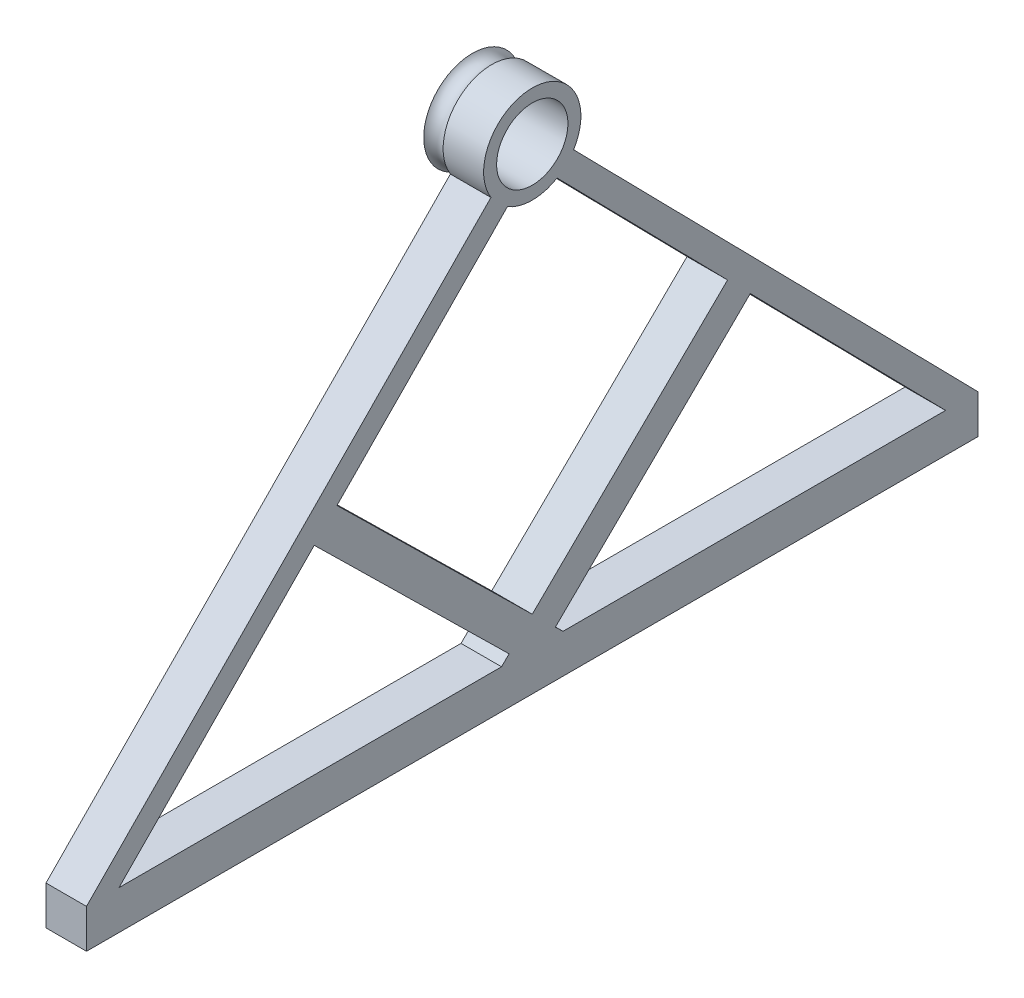
SolidWorks part; units mm, degrees
ref_plane "Front Plane" through (0, 0, 0) normal (0, 0, 1) x (1, 0, 0)
ref_plane "Top Plane" through (0, 0, 0) normal (0, 1, 0) x (1, 0, 0)
ref_plane "Right Plane" through (0, 0, 0) normal (1, 0, 0) x (0, 0, -1)
sketch "Sketch1" plane through (0, 0, 0) normal (0, 1, 0) x (1, 0, 0)
  line L1 (-152.5, -125) -> (152.5, -125)
  line L2 (-152.5, -125) -> (-152.5, 125)
  line L3 (-152.5, 125) -> (152.5, 125)
  line L4 (152.5, -125) -> (152.5, 125)
  line L5 (-152.5, -125) -> (152.5, 125) construction
  line L6 (-152.5, 125) -> (152.5, -125) construction
  line L7 (-165, -137.5) -> (165, -137.5)
  line L8 (-165, -137.5) -> (-165, 137.5)
  line L9 (-165, 137.5) -> (165, 137.5)
  line L10 (165, -137.5) -> (165, 137.5)
  line L11 (-165, -137.5) -> (165, 137.5) construction
  line L12 (-165, 137.5) -> (165, -137.5) construction
  point P0 (0, 0)
  point P5 (0, 0)
extrude "Boss-Extrude4" add sketch "Sketch1" along normal blind 12
sketch "Sketch2" plane through (165, 0, 0) normal (1, 0, 0) x (0, 0, -1)
  line L0 (0, 12) -> (0, 152) construction
  line L1 (-137.5, 12) -> (137.5, 12) construction
  line L2 (0, 152) -> (-137.5, 12)
  line L3 (-137.5, 12) -> (-127.5, 12)
  line L4 (-127.5, 12) -> (0, 141.8182)
  line L5 (0, 152) -> (137.5, 12)
  line L6 (137.5, 12) -> (127.5, 12)
  line L7 (0, 141.8182) -> (127.5, 12)
extrude "Boss-Extrude6" add sketch "Sketch2" against normal up to surface (12.5 mm away) up to face at (152.5, 6, 0)
sketch "Sketch5" plane through (-165, 0, 0) normal (-1, 0, 0) x (0, 0, 1)
  line L0 (0, 12) -> (0, 152) construction
  line L1 (-137.5, 12) -> (137.5, 12) construction
  line L2 (0, 152) -> (-137.5, 12)
  line L3 (-137.5, 12) -> (-127.5, 12)
  line L4 (-127.5, 12) -> (0, 141.8182)
  line L5 (0, 152) -> (137.5, 12)
  line L6 (137.5, 12) -> (127.5, 12)
  line L7 (127.5, 12) -> (0, 141.8182)
extrude "Boss-Extrude7" add sketch "Sketch5" against normal up to surface (12.5 mm away) up to face at (-152.5, 6, 0)
sketch "Sketch6" plane through (152.5, 0, 0) normal (-1, 0, 0) x (0, 0, 1)
  line L0 (0, 152) -> (0, 141.8182) construction
  circle A0 centre (0, 146.9091) radius 11
  circle A1 centre (0, 146.9091) radius 15
extrude "Boss-Extrude8" add sketch "Sketch6" against normal up to surface (12.5 mm away) up to face at (165, 55.2727, 0)
sketch "Sketch7" plane through (152.5, 0, 0) normal (-1, 0, 0) x (0, 0, 1)
  line L0 (0, 152) -> (0, 141.8182) construction
  circle A0 centre (0, 146.9091) radius 11
extrude "Cut-Extrude2" cut sketch "Sketch7" against normal through all
sketch "Sketch8" plane through (0, 69.6316, 70.8976) normal (0, -0.7007, -0.7134) x (-1, 0, 0)
  line L0 (152.5, 101.1799) -> (152.5, -80.7789) construction
  line L1 (152.5, -80.7789) -> (-152.5, -80.7789) construction
  line L2 (-152.5, -80.7789) -> (0, -80.7789) construction
  line L3 (0, -80.7789) -> (0, 71.6699) construction
  line L4 (165, 101.1799) -> (165, -80.7789) construction
  line L5 (140, 15.2005) -> (165, 15.2005)
  line L6 (140, 15.2005) -> (140, 5.2005)
  line L7 (140, 5.2005) -> (165, 5.2005)
  line L8 (165, 15.2005) -> (165, 5.2005)
  line L9 (140, 15.2005) -> (165, 5.2005) construction
  line L10 (140, 5.2005) -> (165, 15.2005) construction
  line L11 (152.5, 15.2005) -> (152.5, 5.2005)
  line L12 (-140, 5.2005) -> (-165, 5.2005)
  line L13 (-165, 15.2005) -> (-165, 5.2005)
  line L14 (-140, 15.2005) -> (-165, 15.2005)
  line L15 (-140, 15.2005) -> (-140, 5.2005)
  line L16 (-152.5, 15.2005) -> (-152.5, 5.2005)
  point P4 (152.5, 10.2005)
  line M7 (152.5, 101.1799) -> (152.5, -80.7789)
  line M9 (165, -80.7789) -> (165, 101.1799)
extrude "Boss-Extrude9" add sketch "Sketch8" along normal up to surface (87.5427 mm away) contours L16 L14 L13 L12 | L7 L5 M7 M9
sketch "Sketch9" plane through (0, 69.6316, -70.8976) normal (0, -0.7007, 0.7134) x (1, 0, 0)
  line L0 (-152.5, 101.1799) -> (-152.5, -80.7789) construction
  line L1 (-152.5, -80.7789) -> (152.5, -80.7789) construction
  line L2 (152.5, -80.7789) -> (0, -80.7789) construction
  line L3 (0, -80.7789) -> (0, 71.5896) construction
  line L4 (-165, -80.7789) -> (-165, 101.1799) construction
  line L5 (-140, 5.2005) -> (-165, 5.2005)
  line L6 (-140, 5.2005) -> (-140, 15.2005)
  line L7 (-140, 15.2005) -> (-165, 15.2005)
  line L8 (-165, 5.2005) -> (-165, 15.2005)
  line L9 (-140, 5.2005) -> (-165, 15.2005) construction
  line L10 (-140, 15.2005) -> (-165, 5.2005) construction
  line L11 (-152.5, 5.2005) -> (-152.5, 15.2005)
  line L12 (140, 15.2005) -> (165, 15.2005)
  line L13 (165, 5.2005) -> (165, 15.2005)
  line L14 (140, 5.2005) -> (165, 5.2005)
  line L15 (140, 5.2005) -> (140, 15.2005)
  line L16 (152.5, 5.2005) -> (152.5, 15.2005)
  point P9 (-152.5, 10.2005)
  line M7 (-152.5, -80.7789) -> (-152.5, 101.1799)
  line M9 (-165, 101.1799) -> (-165, -80.7789)
extrude "Boss-Extrude10" add sketch "Sketch9" along normal up to surface (87.5427 mm away) contours L7 L5 M7 M9 | L16 L14 L13 L12
sketch "Sketch10" plane through (-152.5, 0, 0) normal (1, 0, 0) x (0, 0, -1)
  line L0 (0, 152) -> (0, 141.8182) construction
  line L2 (-12.5, 134.4091) -> (12.5, 134.4091)
  line L3 (-12.5, 134.4091) -> (-12.5, 159.4091)
  line L4 (-12.5, 159.4091) -> (12.5, 159.4091)
  line L5 (12.5, 134.4091) -> (12.5, 159.4091)
  line L6 (-12.5, 134.4091) -> (12.5, 159.4091) construction
  line L7 (-12.5, 159.4091) -> (12.5, 134.4091) construction
  point P4 (0, 146.9091)
extrude "Boss-Extrude11" add sketch "Sketch10" against normal up to surface (12.5 mm away) up to face at (-165, 27.9098, 52.841)
sketch "Sketch11" plane through (0, 0, 0) normal (0, 0, 1) x (1, 0, 0)
  line L0 (152.5, 157.9091) -> (152.5, 135.9091) construction
  line L1 (152.5, 161.9091) -> (146.5169, 161.9091)
  line L2 (152.5, 161.9091) -> (152.5, 157.9091)
  line L3 (152.5, 157.9091) -> (146.5169, 157.9091)
  line L4 (146.5169, 161.9091) -> (146.5169, 157.9091)
  line L5 (152.5, 146.9091) -> (128.8664, 146.9091) construction
  circle A0 centre (149.5084, 163.7989) radius 3.5385
revolve "Revolve1" add sketch "Sketch11" angle 360 about L5
sketch "Sketch12" plane through (-165, 0, 0) normal (-1, 0, 0) x (0, 0, 1)
  line L1 (-137.5, 0) -> (143.4567, 0)
  line L2 (-137.5, 0) -> (-137.5, 169.507)
  line L3 (-137.5, 169.507) -> (143.4567, 169.507)
  line L4 (143.4567, 0) -> (143.4567, 169.507)
extrude "Cut-Extrude3" cut sketch "Sketch12" against normal blind 311
sketch "Sketch13" plane through (146, 0, 0) normal (-1, 0, 0) x (0, 0, 1)
  line L1 (-137.5, 0) -> (157.3863, 0)
  line L2 (-137.5, 0) -> (-137.5, 76.8842)
  line L3 (-137.5, 76.8842) -> (157.3863, 76.8842)
  line L4 (157.3863, 0) -> (157.3863, 76.8842)
extrude "Cut-Extrude4" cut sketch "Sketch13" against normal blind 6.5 and the other way blind 12
